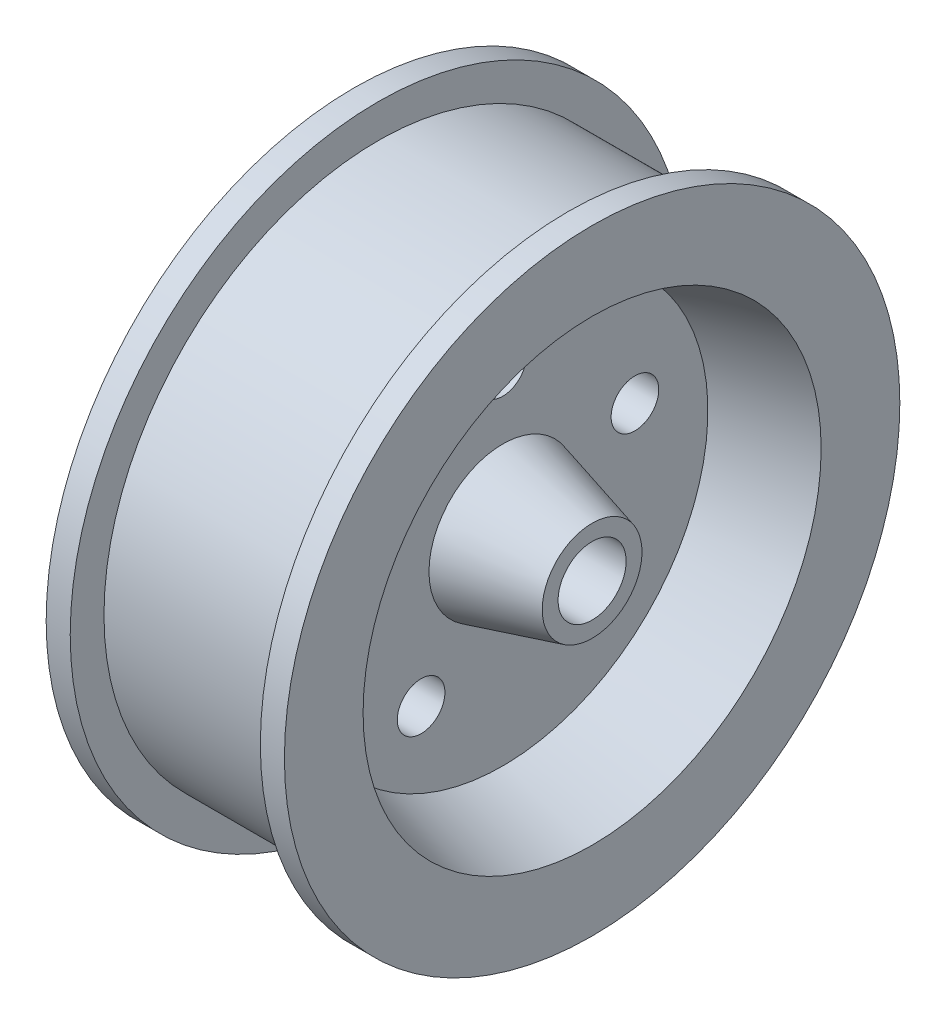
SolidWorks part; units mm, degrees
ref_plane "Plano frontal" through (0, 0, 0) normal (0, 0, 1) x (1, 0, 0)
ref_plane "Plano superior" through (0, 0, 0) normal (0, 1, 0) x (1, 0, 0)
ref_plane "Plano direito" through (0, 0, 0) normal (1, 0, 0) x (0, 0, -1)
sketch "Esboço1" plane through (0, 0, 0) normal (0, 0, 1) x (1, 0, 0)
  line L0 (0, 0) -> (38.1, 0) construction
  line L1 (0, 10.8857) -> (76.2, 10.8857)
  line L2 (38.1, 10.8857) -> (38.1, 87.63) construction
  line L3 (68.5049, 87.63) -> (7.6951, 87.63)
  line L4 (7.6951, 87.63) -> (7.6951, 98.425)
  line L5 (7.6951, 98.425) -> (0, 98.425)
  line L6 (0, 98.425) -> (0, 73.2556)
  line L7 (0, 73.2556) -> (28.575, 65.599)
  line L8 (28.575, 65.599) -> (28.575, 23.6099)
  line L9 (28.575, 23.6099) -> (0, 15.9532)
  line L10 (0, 15.9532) -> (0, 10.8857)
  line L11 (76.2, 15.9532) -> (76.2, 10.8857)
  line L12 (47.625, 23.6099) -> (76.2, 15.9532)
  line L13 (47.625, 65.599) -> (47.625, 23.6099)
  line L14 (76.2, 73.2556) -> (47.625, 65.599)
  line L15 (76.2, 98.425) -> (76.2, 73.2556)
  line L16 (68.5049, 98.425) -> (76.2, 98.425)
  line L17 (68.5049, 87.63) -> (68.5049, 98.425)
  dimension "D1" = 38.1
  dimension "D2" = 98.425
  dimension "D3" = 175.26
  dimension "D4" = 9.525
  dimension "D5" = 75
  dimension "D6" = 75
  dimension "D7" = 57.3024
revolve "Revolução1" add sketch "Esboço1" angle 360 about L0
sketch "Esboço2" plane through (28.575, 0, 0) normal (-1, 0, 0) x (0, 0, 1)
  circle A1 centre (0, 44.45) radius 7.62
  dimension "D1" = 44.45
extrude "Corte-extrusão1" cut sketch "Esboço2" against normal blind 162
pattern_circular "PadrãoCircular1" count 5 over 360 about axis through (0, 0, 0) along (1, 0, 0) of "Corte-extrusão1"
